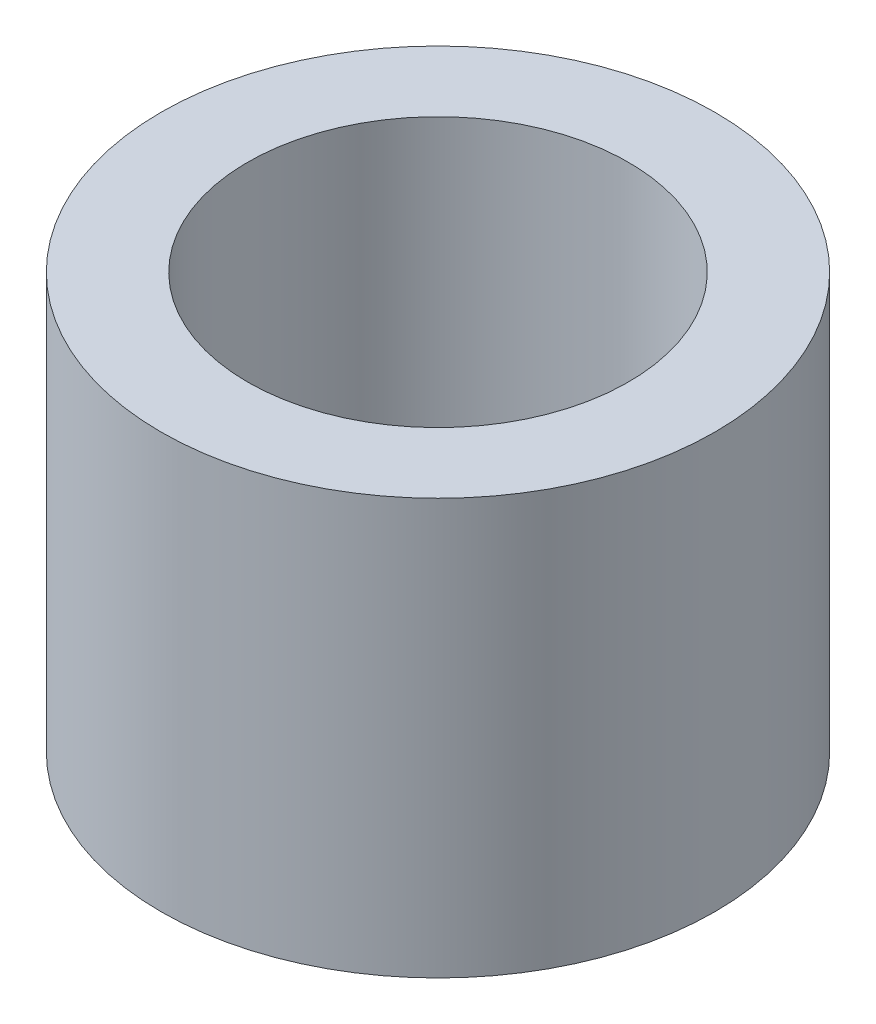
SolidWorks part; units mm, degrees
ref_plane "Front Plane" through (0, 0, 0) normal (0, 0, 1) x (1, 0, 0)
ref_plane "Top Plane" through (0, 0, 0) normal (0, 1, 0) x (1, 0, 0)
ref_plane "Right Plane" through (0, 0, 0) normal (1, 0, 0) x (0, 0, -1)
sketch "Sketch1" plane through (0, 0, 0) normal (0, 1, 0) x (1, 0, 0)
  circle A0 centre (0, 0) radius 11
  circle A1 centre (0, 0) radius 16
extrude "Boss-Extrude1" add sketch "Sketch1" along normal blind 24
